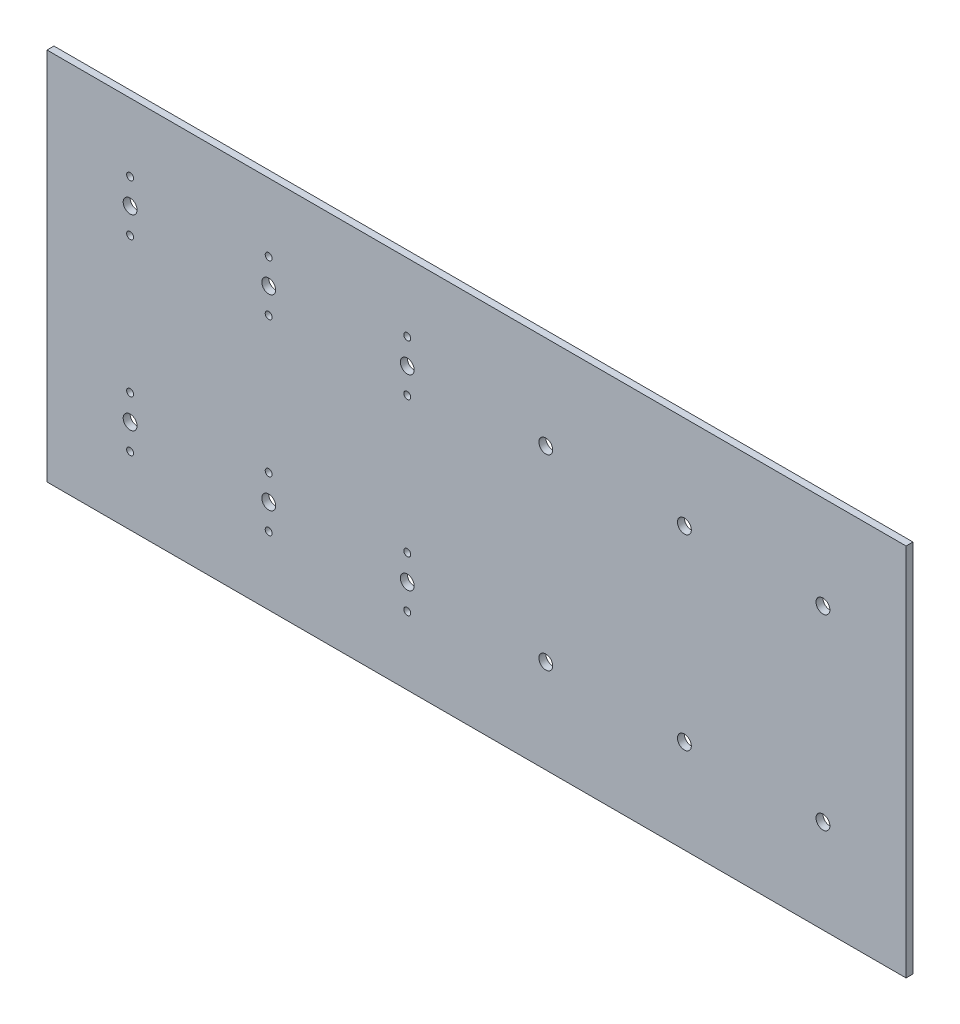
SolidWorks part; units mm, degrees
ref_plane "前视基准面" through (0, 0, 0) normal (0, 0, 1) x (1, 0, 0)
ref_plane "上视基准面" through (0, 0, 0) normal (0, 1, 0) x (1, 0, 0)
ref_plane "右视基准面" through (0, 0, 0) normal (1, 0, 0) x (0, 0, -1)
sketch "草图1" plane through (0, 0, 0) normal (0, 0, 1) x (1, 0, 0)
  line L1 (-10, 10) -> (610, 10)
  line L2 (-10, 10) -> (-10, -260)
  line L3 (-10, -260) -> (610, -260)
  line L4 (610, 10) -> (610, -260)
  dimension "D1" = 610
  dimension "D2" = 10
  dimension "D3" = 10
  dimension "D4" = 260
extrude "凸台-拉伸1" add sketch "草图1" along normal blind 5
sketch "草图2" plane through (0, 0, 0) normal (0, 0, -1) x (-1, 0, 0)
  line L0 (10, -125) -> (-610, -125) construction
  line L1 (10, 10) -> (10, -260) construction
  line L2 (-610, -260) -> (-610, 10) construction
  line L3 (-300, -260) -> (-300, 10) construction
  line L4 (10, -260) -> (-610, -260) construction
  line L5 (-610, 10) -> (10, 10) construction
  line L6 (10, -125) -> (10, -260) construction
  line L7 (10, -192.5) -> (-610, -192.5) construction
  line L8 (-50, -57.5) -> (-50, -75.9) construction
  line L9 (-50, -57.5) -> (18.4037, -57.5) construction
  line L10 (-150, -57.5) -> (-150, -192.5) construction
  line L11 (-150, -57.5) -> (-50, -57.5) construction
  line L12 (-100, -57.5) -> (-100, -125) construction
  circle A0 centre (-50, -192.5) radius 5
  circle A1 centre (-150, -192.5) radius 5
  circle A2 centre (-250, -192.5) radius 5
  circle A3 centre (-350, -192.5) radius 5
  circle A4 centre (-450, -192.5) radius 5
  circle A5 centre (-550, -192.5) radius 5
  circle A6 centre (-550, -57.5) radius 5
  circle A7 centre (-450, -57.5) radius 5
  circle A8 centre (-350, -57.5) radius 5
  circle A9 centre (-250, -57.5) radius 5
  circle A10 centre (-150, -57.5) radius 5
  circle A11 centre (-50, -57.5) radius 5
  circle A12 centre (-50, -75.9) radius 2.5
  circle A13 centre (-50, -39.1) radius 2.5
  circle A14 centre (-50, -210.9) radius 2.5
  circle A15 centre (-50, -174.1) radius 2.5
  circle A16 centre (-250, -210.9) radius 2.5
  circle A17 centre (-250, -174.1) radius 2.5
  circle A18 centre (-250, -75.9) radius 2.5
  circle A19 centre (-250, -39.1) radius 2.5
  circle A20 centre (-150, -75.9) radius 2.5
  circle A21 centre (-150, -39.1) radius 2.5
  circle A22 centre (-150, -210.9) radius 2.5
  circle A23 centre (-150, -174.1) radius 2.5
  point P16 (-50, -192.5)
  point P17 (-150, -192.5)
  point P18 (-250, -192.5)
  point P19 (-350, -192.5)
  point P20 (-450, -192.5)
  point P21 (-550, -192.5)
  point P22 (-550, -57.5)
  point P23 (-450, -57.5)
  point P24 (-350, -57.5)
  point P25 (-250, -57.5)
  point P26 (-150, -57.5)
  point P27 (-50, -57.5)
  dimension "D4" = 10
  dimension "D5" = 5
  dimension "D1" = 100
  dimension "D2" = 100
  dimension "D3" = 100
  dimension "D6" = 18.4
extrude "切除-拉伸1" cut sketch "草图2" against normal through all
